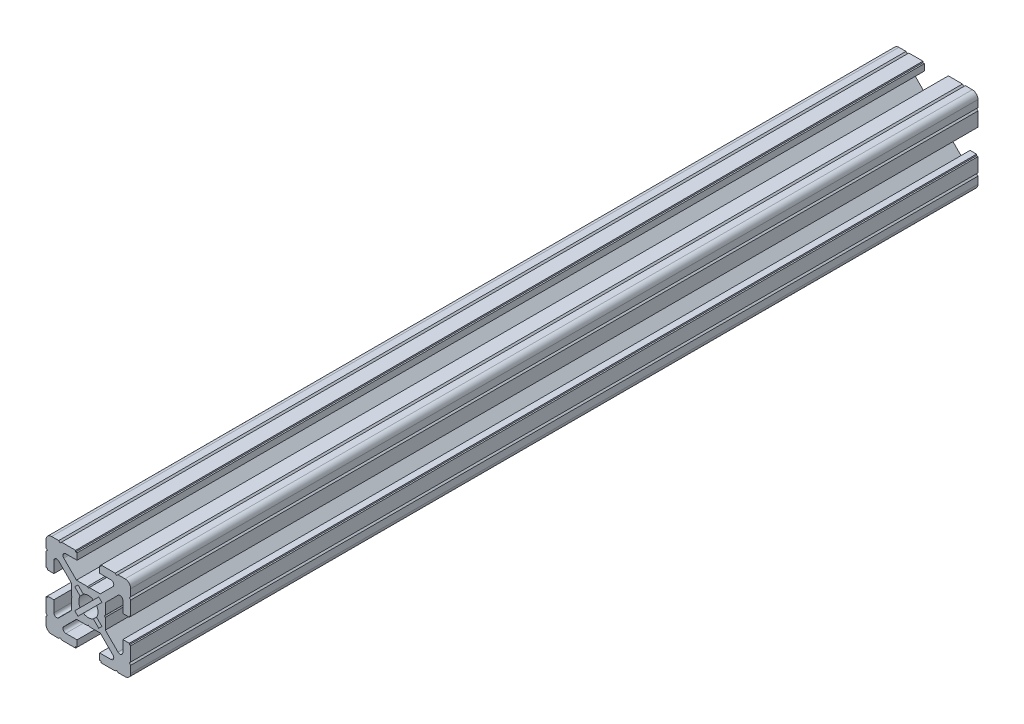
SolidWorks part; units mm, degrees
material "1060 Alloy"
ref_plane "Front" through (0, 0, 0) normal (0, 0, 1) x (1, 0, 0)
ref_plane "Top" through (0, 0, 0) normal (0, 1, 0) x (1, 0, 0)
ref_plane "Right" through (0, 0, 0) normal (1, 0, 0) x (0, 0, -1)
sketch "Sketch1" plane through (0, 0, 0) normal (0, 0, 1) x (1, 0, 0)
  line L0 (-2.9023, 1.771) -> (-4.8083, 3.677)
  line L1 (-4.8083, 3.677) -> (-3.677, 4.8083)
  line L2 (-3.677, 4.8083) -> (-1.771, 2.9023)
  line L3 (1.771, 2.9023) -> (3.677, 4.8083)
  line L4 (3.677, 4.8083) -> (4.8083, 3.677)
  line L5 (4.8083, 3.677) -> (2.9023, 1.771)
  line L6 (2.9023, -1.771) -> (4.8083, -3.677)
  line L7 (4.8083, -3.677) -> (3.677, -4.8083)
  line L8 (3.677, -4.8083) -> (1.771, -2.9023)
  line L9 (-1.771, -2.9023) -> (-3.677, -4.8083)
  line L10 (-3.677, -4.8083) -> (-4.8083, -3.677)
  line L11 (-4.8083, -3.677) -> (-2.9023, -1.771)
  line L12 (13, 15) -> (10.5, 15)
  line L13 (10.5, 15) -> (10, 14.5)
  line L14 (10, 14.5) -> (9.5, 15)
  line L15 (9.5, 15) -> (4.5, 15)
  line L16 (4.5, 15) -> (4.5, 14.5)
  line L17 (4.5, 14.5) -> (4, 14.5)
  line L18 (4, 14.5) -> (4, 12.2)
  line L19 (4, 12.2) -> (8, 12.2)
  line L20 (8.7071, 10.4929) -> (4.2142, 6)
  line L21 (4.2142, 6) -> (0.3125, 6)
  line L22 (0.3125, 6) -> (0, 5.7)
  line L23 (0, 5.7) -> (-0.3125, 6)
  line L24 (-0.3125, 6) -> (-4.2142, 6)
  line L25 (-4.2142, 6) -> (-8.7071, 10.4929)
  line L26 (-8, 12.2) -> (-4, 12.2)
  line L27 (-4, 12.2) -> (-4, 14.5)
  line L28 (-4, 14.5) -> (-4.5, 14.5)
  line L29 (-4.5, 14.5) -> (-4.5, 15)
  line L30 (-4.5, 15) -> (-9.5, 15)
  line L31 (-9.5, 15) -> (-10, 14.5)
  line L32 (-10, 14.5) -> (-10.5, 15)
  line L33 (-10.5, 15) -> (-13, 15)
  line L34 (-15, 13) -> (-15, 10.5)
  line L35 (-15, 10.5) -> (-14.5, 10)
  line L36 (-14.5, 10) -> (-15, 9.5)
  line L37 (-15, 9.5) -> (-15, 4.5)
  line L38 (-15, 4.5) -> (-14.5, 4.5)
  line L39 (-14.5, 4.5) -> (-14.5, 4)
  line L40 (-14.5, 4) -> (-12.2, 4)
  line L41 (-12.2, 4) -> (-12.2, 8)
  line L42 (-10.4929, 8.7071) -> (-6, 4.2142)
  line L43 (-6, 4.2142) -> (-6, 0.3125)
  line L44 (-6, 0.3125) -> (-5.7, 0)
  line L45 (-5.7, 0) -> (-6, -0.3125)
  line L46 (-6, -0.3125) -> (-6, -4.2142)
  line L47 (-6, -4.2142) -> (-10.4929, -8.7071)
  line L48 (-12.2, -8) -> (-12.2, -4)
  line L49 (-12.2, -4) -> (-14.5, -4)
  line L50 (-14.5, -4) -> (-14.5, -4.5)
  line L51 (-14.5, -4.5) -> (-15, -4.5)
  line L52 (-15, -4.5) -> (-15, -9.5)
  line L53 (-15, -9.5) -> (-14.5, -10)
  line L54 (-14.5, -10) -> (-15, -10.5)
  line L55 (-15, -10.5) -> (-15, -13)
  line L56 (-13, -15) -> (-10.4899, -15)
  line L57 (-10.4899, -15) -> (-9.9899, -14.5)
  line L58 (-9.9899, -14.5) -> (-9.5, -15)
  line L59 (-9.5, -15) -> (-4.5, -15)
  line L60 (-4.5, -15) -> (-4.5, -14.5)
  line L61 (-4.5, -14.5) -> (-4, -14.5)
  line L62 (-4, -14.5) -> (-4, -12.2)
  line L63 (-4, -12.2) -> (-8, -12.2)
  line L64 (-8.7071, -10.4929) -> (-4.2142, -6)
  line L65 (-4.2142, -6) -> (-0.3125, -6)
  line L66 (-0.3125, -6) -> (0, -5.7)
  line L67 (0, -5.7) -> (0.3125, -6)
  line L68 (0.3125, -6) -> (4.2142, -6)
  line L69 (4.2142, -6) -> (8.7071, -10.4929)
  line L70 (8, -12.2) -> (4, -12.2)
  line L71 (4, -12.2) -> (4, -14.5)
  line L72 (4, -14.5) -> (4.5, -14.5)
  line L73 (4.5, -14.5) -> (4.5, -15)
  line L74 (4.5, -15) -> (9.5, -15)
  line L75 (9.5, -15) -> (10, -14.5)
  line L76 (10, -14.5) -> (10.5, -15)
  line L77 (10.5, -15) -> (13, -15)
  line L78 (15, -13) -> (15, -10.5)
  line L79 (15, -10.5) -> (14.5, -10)
  line L80 (14.5, -10) -> (15, -9.5)
  line L81 (15, -9.5) -> (15, -4.5)
  line L82 (15, -4.5) -> (14.5, -4.5)
  line L83 (14.5, -4.5) -> (14.5, -4)
  line L84 (14.5, -4) -> (12.2, -4)
  line L85 (12.2, -4) -> (12.2, -8)
  line L86 (10.4929, -8.7071) -> (6, -4.2142)
  line L87 (6, -4.2142) -> (6, -0.3125)
  line L88 (6, -0.3125) -> (5.7, 0)
  line L89 (5.7, 0) -> (6, 0.3125)
  line L90 (6, 0.3125) -> (6, 4.2142)
  line L91 (6, 4.2142) -> (10.4929, 8.7071)
  line L92 (12.2, 8) -> (12.2, 4)
  line L93 (12.2, 4) -> (14.5, 4)
  line L94 (14.5, 4) -> (14.5, 4.5)
  line L95 (14.5, 4.5) -> (15, 4.5)
  line L96 (15, 4.5) -> (15, 9.5)
  line L97 (15, 9.5) -> (14.5, 10)
  line L98 (14.5, 10) -> (15, 10.5)
  line L99 (15, 10.5) -> (15, 13)
  arc A0 (-1.771, 2.9023) -> (1.771, 2.9023) centre (0, 0) cw
  arc A1 (2.9023, 1.771) -> (2.9023, -1.771) centre (0, 0) cw
  arc A2 (1.771, -2.9023) -> (-1.771, -2.9023) centre (0, 0) cw
  arc A3 (-2.9023, -1.771) -> (-2.9023, 1.771) centre (0, 0) cw
  arc A4 (8, 12.2) -> (8.7071, 10.4929) centre (8, 11.2) cw
  arc A5 (-8.7071, 10.4929) -> (-8, 12.2) centre (-8, 11.2) cw
  arc A6 (-13, 15) -> (-15, 13) centre (-13, 13) ccw
  arc A7 (-12.2, 8) -> (-10.4929, 8.7071) centre (-11.2, 8) cw
  arc A8 (-10.4929, -8.7071) -> (-12.2, -8) centre (-11.2, -8) cw
  arc A9 (-15, -13) -> (-13, -15) centre (-13, -13) ccw
  arc A10 (-8, -12.2) -> (-8.7071, -10.4929) centre (-8, -11.2) cw
  arc A11 (8.7071, -10.4929) -> (8, -12.2) centre (8, -11.2) cw
  arc A12 (13, -15) -> (15, -13) centre (13, -13) ccw
  arc A13 (12.2, -8) -> (10.4929, -8.7071) centre (11.2, -8) cw
  arc A14 (10.4929, 8.7071) -> (12.2, 8) centre (11.2, 8) cw
  arc A15 (15, 13) -> (13, 15) centre (13, 13) ccw
  dimension "D3" = 3.4
  dimension "D7" = 2
  dimension "D1" = 30
  dimension "D2" = 30
  dimension "D4" = 9
  dimension "D5" = 9
  dimension "D6" = 8
  dimension "D8" = 2.8
extrude "Boss-Extrude1" add sketch "Sketch1" along normal blind 300
